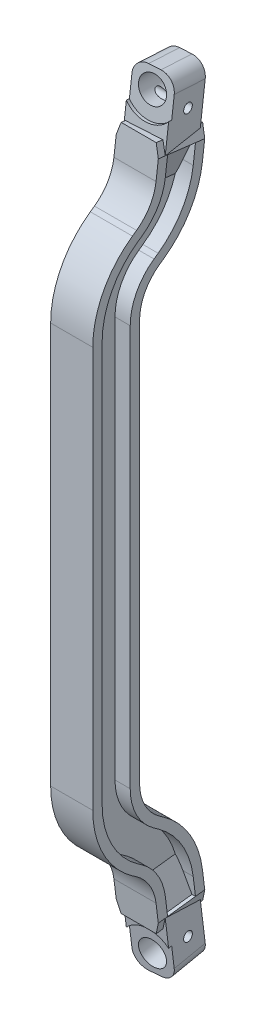
SolidWorks part; units mm, degrees
material "AISI 1045 Steel, cold drawn"
ref_plane "Front Plane" through (0, 0, 0) normal (0, 0, 1) x (1, 0, 0)
ref_plane "Top Plane" through (0, 0, 0) normal (0, 1, 0) x (1, 0, 0)
ref_plane "Right Plane" through (0, 0, 0) normal (1, 0, 0) x (0, 0, -1)
sketch "Sketch1" plane through (0, 0, 0) normal (0, 1, 0) x (1, 0, 0)
  line L0 (-45, 0) -> (-45, -20)
  line L1 (-45, -20) -> (-12.5, -20)
  line L2 (-12.5, -20) -> (-12.5, -80)
  line L3 (-12.5, -80) -> (-45, -80)
  line L4 (-45, -80) -> (-45, -100)
  line L5 (-45, -100) -> (45, -100)
  line L6 (0, 26.9753) -> (0, -89.5452) construction
  line L7 (45, 0) -> (-45, 0)
  line L8 (45, -100) -> (45, -80)
  line L9 (45, -80) -> (12.5, -80)
  line L10 (12.5, -20) -> (12.5, -80)
  line L11 (45, -20) -> (12.5, -20)
  line L12 (45, 0) -> (45, -20)
  point P12 (0, 0)
  dimension "D1" = 20
  dimension "D2" = 20
  dimension "D3" = 60
  dimension "D4" = 90
  dimension "D6" = 25
sketch "Sketch2" plane through (0, 0, 0) normal (1, 0, 0) x (0, 0, -1)
  line L0 (35.15, -667.615) -> (40, -707.115)
  line L1 (-6.4683, -598.0826) -> (-15.2727, -591.8729)
  line L2 (-100, -428.4342) -> (-100, -372.115)
  line L3 (-100, -372.115) -> (-100, 0)
  line L4 (-100, 0) -> (-80, 0) construction
  line L5 (-80, 0) -> (-100, 0) construction
  arc A0 (35.15, -667.615) -> (-6.4683, -598.0826) centre (-64.1046, -679.8019) ccw
  arc A1 (-15.2727, -591.8729) -> (-100, -428.4342) centre (100, -428.4342) cw
  point P9 (-100, -532.115)
  dimension "D4" = 100
  dimension "D5" = 200
  dimension "D1" = 7
  dimension "D2" = 160
  dimension "D3" = 140
  dimension "D6" = 372.115
  dimension "D7" = 335
  dimension "D8" = 39.5
sweep "Sweep3" add profiles "Sketch1" path "Sketch2"
sketch "Sketch6" plane through (0, 6.5232, -53.1272) normal (0, 0.1219, -0.9925) x (-1, 0, 0)
  line L0 (-45, -706.719) -> (45, -706.719)
  line L1 (45, -706.719) -> (37.5, -731.719)
  line L2 (37.5, -731.719) -> (-37.5, -731.719)
  line L3 (-37.5, -731.719) -> (-45, -706.719)
  point P4 (0, -731.719)
  point P7 (0, -706.719)
  dimension "D1" = 25
  dimension "D2" = 75
extrude "Boss-Extrude3" add sketch "Sketch6" against normal blind 100
sketch "Sketch7" plane through (0, -726.2649, -89.1741) normal (0, -0.9925, -0.1219) x (1, 0, 0)
  line L0 (-39.4892, 37.4738) -> (45, 31.5657)
  line L1 (45, 31.5657) -> (39.4892, -47.2418)
  line L2 (39.4892, -47.2418) -> (-45, -41.3338)
  line L3 (-45, -41.3338) -> (-39.4892, 37.4738)
  line L4 (-45, 46.4738) -> (45, 46.4738) construction
  line L6 (-45, -53.5262) -> (-45, -33.5262) construction
  line L7 (37.5, 46.4738) -> (-37.5, 46.4738) construction
  line L10 (45, 26.4738) -> (45, -33.5262) construction
  dimension "D1" = 4
  dimension "D2" = 79
  dimension "D3" = 9
  dimension "D4" = 90
extrude "Boss-Extrude4" add sketch "Sketch7" along normal blind 110 and the other way up to next
fillet "Fillet2" radius 30 2 edges at (42.2446, -834.4898, -110.3594) (-42.2446, -835.2098, -104.4953)
sketch "Sketch8" plane through (-3.0952, 5.3944, -43.9341) normal (-0.0698, 0.1216, -0.9901) x (-0.9976, -0.0084, 0.0693)
  line L3 (11.9032, -841.7205) -> (-12.7923, -841.7175) construction
  circle A0 centre (-0.4446, -801.719) radius 28
  point P2 (-0.4446, -841.719)
  dimension "D2" = 56
  dimension "D1" = 40
extrude "Cut-Extrude2" cut sketch "Sketch8" against normal blind 85
chamfer "Chamfer2" distance 25 angle 70 2 edges at (12.5, -701.0215, -89.6273) (-12.5, -701.0215, -89.6273)
sketch "Sketch9" plane through (-41.9048, -0.3571, 2.9084) normal (-0.9976, -0.0085, 0.0692) x (0.0692, 0.0006, 0.9976)
  line L0 (-63.5715, -799.9445) -> (-141.9798, -790.2937) construction
  line L1 (-143.2014, -800.2188) -> (-130.3743, -696.0052) construction
  circle A0 centre (-103.8214, -766.7791) radius 10
  dimension "D2" = 20
  dimension "D1" = 28
  dimension "D3" = 35
extrude "Cut-Extrude3" cut sketch "Sketch9" against normal through all
mirror "Mirror1" about plane through (0, 0, 0) normal (0, 1, 0) of "Cut-Extrude3", "Chamfer2", "Cut-Extrude2", "Fillet2", "Boss-Extrude4", "Boss-Extrude3", "Sweep3"
sketch "Sketch10" plane through (2.4155, 4.2098, 34.286) normal (0.0698, 0.1216, 0.9901) x (0.9976, -0.0085, -0.0692)
  circle A0 centre (0.3456, 801.719) radius 55
  dimension "D1" = 110
extrude "Cut-Extrude4" cut sketch "Sketch10" against normal blind 7
sketch "Sketch11" plane through (2.4155, -4.2098, 34.286) normal (0.0698, -0.1216, 0.9901) x (0.9976, 0.0085, -0.0692)
  circle A0 centre (0.3456, -801.719) radius 55
  dimension "D1" = 110
extrude "Cut-Extrude5" cut sketch "Sketch11" against normal blind 7
